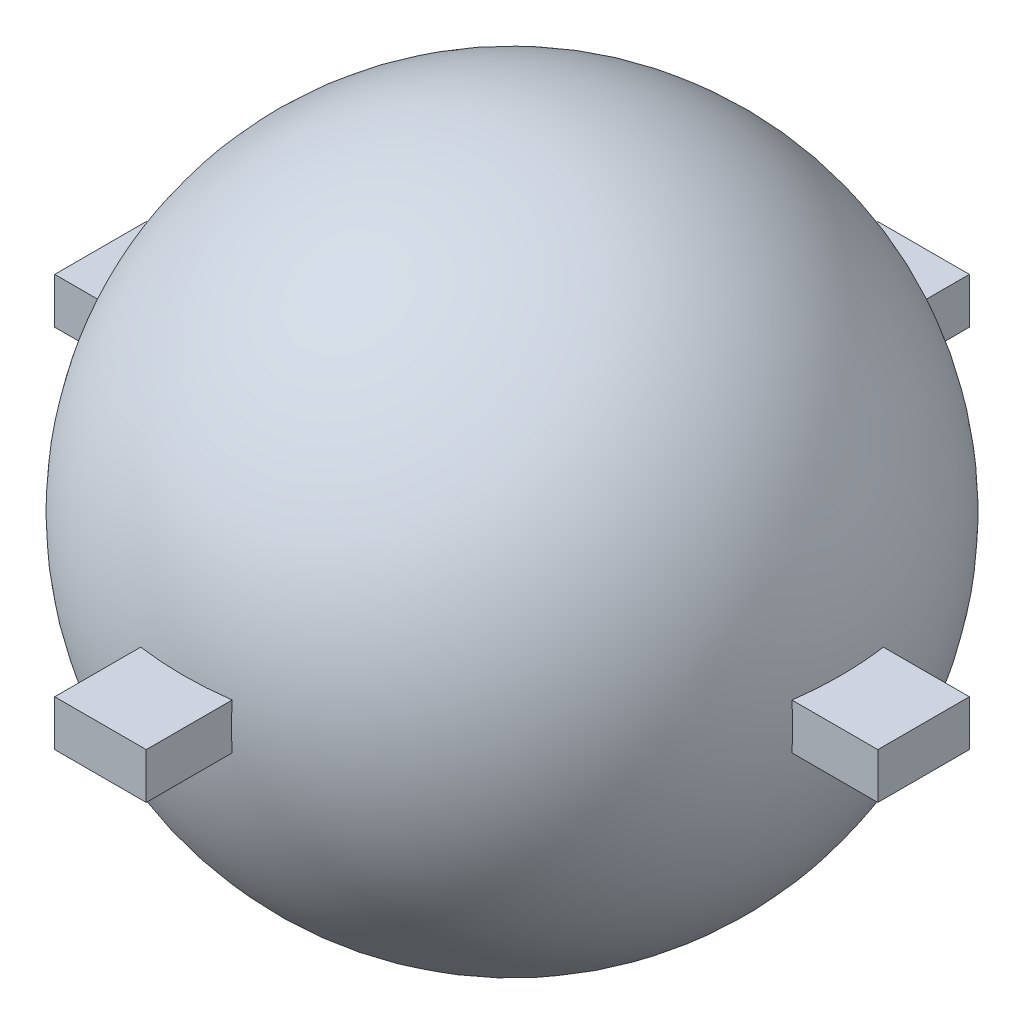
SolidWorks part; units mm, degrees
material "6061 Alloy"
ref_plane "Front Plane" through (0, 0, 0) normal (0, 0, 1) x (1, 0, 0)
ref_plane "Top Plane" through (0, 0, 0) normal (0, 1, 0) x (1, 0, 0)
ref_plane "Right Plane" through (0, 0, 0) normal (1, 0, 0) x (0, 0, -1)
sketch "Sketch1" plane through (0, 0, 0) normal (0, 1, 0) x (1, 0, 0)
  line L0 (0, 0) -> (341.122, 0) construction
  line L1 (-274.32, 0) -> (274.32, 0)
  arc A0 (274.32, 0) -> (-274.32, 0) centre (0, 0) ccw
  point P7 (341.122, 0)
  dimension "D1" = 548.64
revolve "Revolve6" add sketch "Sketch1" angle 360 about L1
shell "Shell1" thickness 3.175
sketch "Sketch2" plane through (0, 0, 0) normal (0, 1, 0) x (1, 0, 0)
  line L0 (-367.919, 0) -> (367.919, 0)
  line L1 (367.919, -152.4) -> (367.919, 152.4)
  line L2 (152.3949, -367.9211) -> (367.9211, -152.3949)
  line L3 (-152.4, -367.919) -> (152.4, -367.919)
  line L4 (-367.9211, -152.3949) -> (-152.3949, -367.9211)
  line L5 (-367.919, 152.4) -> (-367.919, -152.4)
  line L6 (-152.3949, 367.9211) -> (-367.9211, 152.3949)
  line L7 (152.4, 367.919) -> (-152.4, 367.919)
  line L8 (367.9211, 152.3949) -> (152.3949, 367.9211)
  line L9 (141.876, 342.519) -> (-141.876, 342.519)
  line L10 (-141.876, 342.519) -> (-342.519, 141.876)
  line L11 (-342.519, 141.876) -> (-342.519, -141.876)
  line L12 (-342.519, -141.876) -> (-141.876, -342.519)
  line L13 (-141.876, -342.519) -> (141.876, -342.519)
  line L14 (141.876, -342.519) -> (342.519, -141.876)
  line L15 (342.519, -141.876) -> (342.519, 141.876)
  line L16 (342.519, 141.876) -> (141.876, 342.519)
  line L17 (-342.519, 152.4) -> (-342.519, -152.4) construction
  line L18 (-134.4344, 349.9606) -> (-349.9606, 134.4344) construction
  line L19 (152.4, 342.519) -> (-152.4, 342.519) construction
  line L20 (349.9606, 134.4344) -> (134.4344, 349.9606) construction
  line L21 (342.519, -152.4) -> (342.519, 152.4) construction
  line L22 (134.4344, -349.9606) -> (349.9606, -134.4344) construction
  line L23 (-152.4, -342.519) -> (152.4, -342.519) construction
  line L24 (-349.9606, -134.4344) -> (-134.4344, -349.9606) construction
  point P4 (0, 0)
  point P7 (367.919, 0)
  dimension "D1" = 735.838
  dimension "D2" = 304.8
  dimension "D4" = 25.4
  dimension "D3" = 8
sketch "Sketch5" plane through (0, 0, 0) normal (0, 0, 1) x (1, 0, 0)
  line L0 (0, 0) -> (0, -338.0546)
ref_plane "Plane3" through (0, 0, 342.5825) normal (0, 0, 1) x (1, 0, 0)
sketch "Sketch4" plane through (0, 0, 342.5825) normal (0, 0, 1) x (1, 0, 0)
  line L1 (-38.1, -19.05) -> (38.1, -19.05)
  line L2 (-38.1, -19.05) -> (-38.1, 19.05)
  line L3 (-38.1, 19.05) -> (38.1, 19.05)
  line L4 (38.1, -19.05) -> (38.1, 19.05)
  line L5 (-38.1, -19.05) -> (38.1, 19.05) construction
  line L6 (-38.1, 19.05) -> (38.1, -19.05) construction
  point P0 (0, 0)
  dimension "D1" = 76.2
  dimension "D2" = 38.1
extrude "Boss-Extrude1" add sketch "Sketch4" against normal up to surface (71.59 mm away)
pattern_circular "CirPattern1" count 4 over 360 about axis through (0, 0, 0) along (0, 1, 0) of "Boss-Extrude1"
